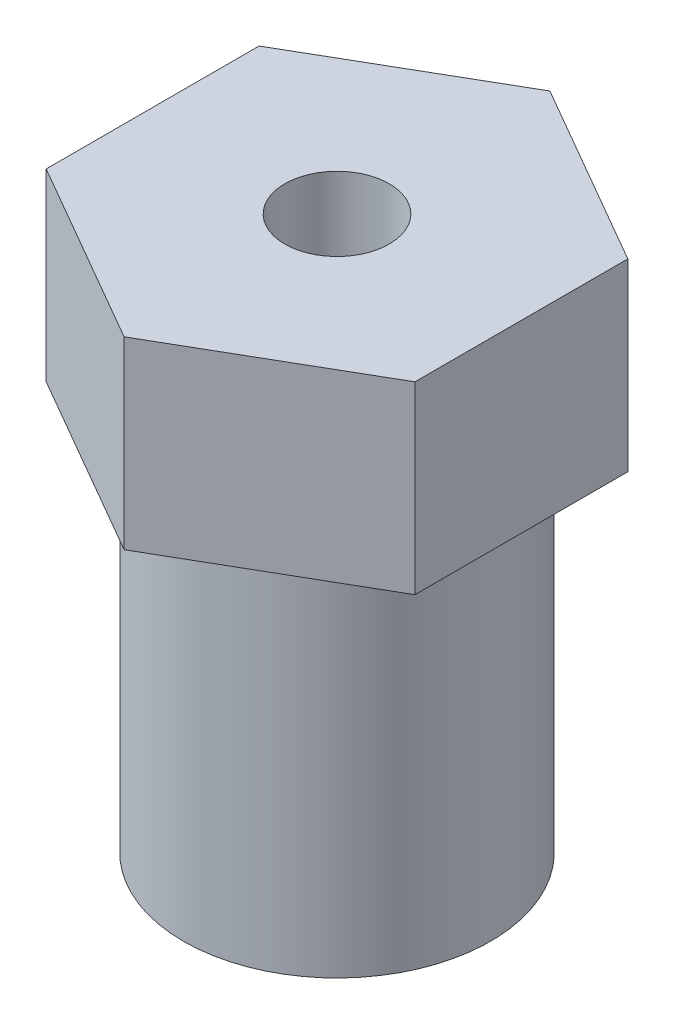
SolidWorks part; units mm, degrees
material "Brass"
ref_plane "Front Plane" through (0, 0, 0) normal (0, 0, 1) x (1, 0, 0)
ref_plane "Top Plane" through (0, 0, 0) normal (0, 1, 0) x (1, 0, 0)
ref_plane "Right Plane" through (0, 0, 0) normal (1, 0, 0) x (0, 0, -1)
sketch "Sketch1" plane through (0, 0, 0) normal (0, 1, 0) x (1, 0, 0)
  circle A0 centre (0, 0) radius 5
  circle A1 centre (0, 0) radius 3
  dimension "D1" = 6
  dimension "D2" = 10
extrude "Boss-Extrude1" add sketch "Sketch1" along normal blind 14
sketch "Sketch2" plane through (0, 14, 0) normal (0, 1, 0) x (1, 0, 0)
  line L1 (0, 6.9282) -> (-6, 3.4641)
  line L2 (-6, 3.4641) -> (-6, -3.4641)
  line L3 (-6, -3.4641) -> (0, -6.9282)
  line L4 (0, -6.9282) -> (6, -3.4641)
  line L5 (6, -3.4641) -> (6, 3.4641)
  line L6 (6, 3.4641) -> (0, 6.9282)
  circle A0 centre (0, 0) radius 6 construction
  dimension "D1" = 12
extrude "Boss-Extrude2" add sketch "Sketch2" along normal blind 4
hole_wizard "M3 Clearance Hole1" positions "Sketch4" profile "Sketch5" hole size "M3" standard "ISO" end condition up to next
sketch "Sketch4" plane through (0, 18, 0) normal (0, 1, 0) x (1, 0, 0)
  point P0 (0, 0)
sketch "Sketch5" plane through (0, 18, 0) normal (1, 0, 0) x (0, 0, 1)
  line L0 (0, 0) -> (0, 4)
  line L1 (0, 4) -> (1.7, 4)
  line L2 (1.7, 4) -> (1.7, 0)
  line L5 (1.7, 0) -> (0, 0)
  line L11 (0, -6.35) -> (0, 107.95) construction
  dimension "Thru Hole Dia." = 3.4
  dimension "Thru Hole Depth" = 4
sketch "Sketch6" plane through (-3, 0, -5.1962) normal (-0.5, 0, -0.866) x (-0.866, 0, 0.5)
  line L1 (-5, 14) -> (-5, 0) construction
  line L2 (-5, 14) -> (-5, 0) construction
  circle A0 centre (0, 6) radius 1.5
  point P7 (0, 6)
  dimension "D2" = 3
  dimension "D1" = 6
hole_wizard "M3 Clearance Hole2" positions "Sketch7" profile "Sketch8" hole size "M3" standard "ISO"
sketch "Sketch7" plane through (-3, 0, -5.1962) normal (-0.5, 0, -0.866) x (-0.866, 0, 0.5)
  point P0 (0, 6)
sketch "Sketch8" plane through (-3, 6, -5.1962) normal (0, 1, 0) x (-0.866, 0, 0.5)
  line L0 (0, 0) -> (0, 3)
  line L1 (0, 3) -> (1.7, 3)
  line L2 (1.7, 3) -> (1.7, 0)
  line L5 (1.7, 0) -> (0, 0)
  line L11 (0, -6.35) -> (0, 107.95) construction
  dimension "Thru Hole Dia." = 3.4
  dimension "Thru Hole Depth" = 3
thread "Thread1" pitch 0.3175 start angle 0, offset 0, length 0, pitch 0.3175, diameter 3.4
ref_plane "Plane1" through (-1.7, 18, 0) normal (0, 0, 1) x (-1, 0, 0)
sketch "Thread Profile1" plane through (-1.7, 18, 0) normal (0, 0, 1) x (-1, 0, 0)
  line L0 (0, 0) -> (0, 0.3175) construction
  line L11 (0, 0) -> (0, 0.2778)
  line L12 (0, 0.2778) -> (-0.1719, 0.1786)
  line L13 (-0.1719, 0.1786) -> (-0.1719, 0.0992)
  line L15 (-0.1719, 0.0992) -> (0, 0)
  line L17 (-0.1719, 0.1389) -> (0, 0.1389) construction
  point P2 (0, 0)
  dimension "Pitch" = 0.3175
  dimension "Profile_Angle" = 60
  dimension "Profile_Land" = 0.0794
  dimension "Profile_Height" = 0.1719
sketch "Sketch11" plane through (-3, 0, -5.1962) normal (-0.5, 0, -0.866) x (-0.866, 0, 0.5)
  circle A0 centre (0, 6) radius 1.7 construction
  circle A1 centre (0, 6) radius 1.7
  circle A2 centre (0, 6) radius 2.5494
extrude "Boss-Extrude3" add sketch "Sketch11" against normal up to surface (1.2979 mm away)
thread "Thread2" pitch 0.3175 start angle 0, offset 0, length 3, pitch 0.3175, diameter 3.4
ref_plane "Plane2" through (-1.5278, 6, -6.0462) normal (0, -1, 0) x (0.866, 0, -0.5)
sketch "Thread Profile2" plane through (-1.5278, 6, -6.0462) normal (0, -1, 0) x (0.866, 0, -0.5)
  line L0 (0, 0) -> (0, 0.3175) construction
  line L11 (0, 0) -> (0, 0.2778)
  line L12 (0, 0.2778) -> (-0.1719, 0.1786)
  line L13 (-0.1719, 0.1786) -> (-0.1719, 0.0992)
  line L15 (-0.1719, 0.0992) -> (0, 0)
  line L17 (-0.1719, 0.1389) -> (0, 0.1389) construction
  point P2 (0, 0)
  dimension "Pitch" = 0.3175
  dimension "Profile_Angle" = 60
  dimension "Profile_Land" = 0.0794
  dimension "Profile_Height" = 0.1719
sketch "Sketch14" plane through (-3, 0, -5.1962) normal (-0.5, 0, -0.866) x (-0.866, 0, 0.5)
  circle A0 centre (0, 6) radius 2.5494 construction
  circle A1 centre (0, 6) radius 2.5494
extrude "Cut-Extrude2" cut sketch "Sketch14" against normal blind 1 contours A1
sketch "Sketch15" plane through (0, 18, 0) normal (0, 1, 0) x (1, 0, 0)
  line L0 (-6, 3.4641) -> (-6, -3.4641) construction
  line L1 (-6, 0) -> (6, 0)
  line L2 (6, -3.4641) -> (6, 3.4641) construction
sketch "Sketch17" plane through (-3, 0, 5.1962) normal (-0.5, 0, 0.866) x (0.866, 0, 0.5)
  line L0 (1.9155, 18) -> (1.9155, 14)
  line L1 (-3.4641, 18) -> (3.4641, 18) construction
  line L2 (-3.4641, 14) -> (3.4641, 14) construction
  line L3 (4.1462, 18) -> (4.1462, 0) construction
sketch "Sketch18" plane through (0, 0, 0) normal (0, 0, 1) x (1, 0, 0)
  line L0 (1.0397, 0) -> (1.0397, 14) construction
  line L1 (-3, 0) -> (3, 0) construction
  line L2 (-1.7, 14) -> (1.7, 14) construction
sketch "Sketch19" plane through (0, 14, 0) normal (0, -1, 0) x (1, 0, 0)
  line L7 (0, -6.9282) -> (6, -3.4641)
  line L8 (6, -3.4641) -> (6, 3.4641)
  line L9 (6, 3.4641) -> (0, 6.9282)
  line L10 (0, 6.9282) -> (-6, 3.4641)
  line L11 (-6, 3.4641) -> (-6, -3.4641)
  line L12 (-6, -3.4641) -> (0, -6.9282)
  line L13 (0, -6.9282) -> (6, -3.4641)
  line L14 (6, -3.4641) -> (6, 3.4641)
  line L15 (6, 3.4641) -> (0, 6.9282)
  line L16 (0, 6.9282) -> (-6, 3.4641)
  line L17 (-6, 3.4641) -> (-6, -3.4641)
  line L18 (-6, -3.4641) -> (0, -6.9282)
  dimension "D1" = 0
extrude "Boss-Extrude4" add sketch "Sketch19" along normal blind 2
